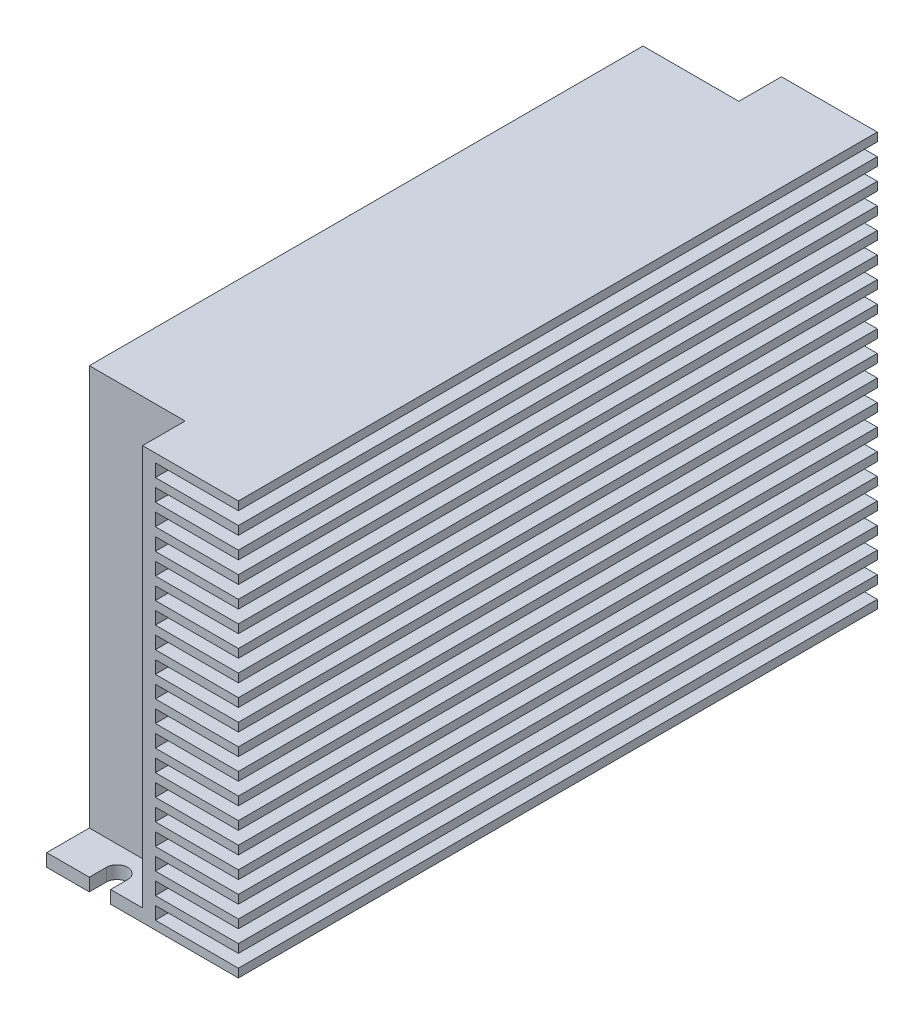
SolidWorks part; units mm, degrees
ref_plane "Front Plane" through (0, 0, 0) normal (0, 0, 1) x (1, 0, 0)
ref_plane "Top Plane" through (0, 0, 0) normal (0, 1, 0) x (1, 0, 0)
ref_plane "Right Plane" through (0, 0, 0) normal (1, 0, 0) x (0, 0, -1)
sketch "Sketch1" plane through (0, 0, 0) normal (0, 1, 0) x (1, 0, 0)
  line L1 (0, 0) -> (45, 0)
  line L2 (0, 0) -> (0, 150)
  line L3 (0, 150) -> (45, 150)
  line L4 (45, 0) -> (45, 150)
  dimension "D1" = 45
  dimension "D2" = 150
extrude "Boss-Extrude1" add sketch "Sketch1" along normal blind 97
sketch "Sketch2" plane through (0, 97, 0) normal (0, 1, 0) x (1, 0, 0)
  line L1 (0, 150) -> (22.5, 150)
  line L2 (0, 150) -> (0, 140)
  line L3 (0, 140) -> (22.5, 140)
  line L4 (22.5, 150) -> (22.5, 140)
  dimension "D1" = 22.5
  dimension "D2" = 10
extrude "Cut-Extrude1" cut sketch "Sketch2" against normal offset from surface (94 mm away) 3 up to face at (22.5, 0, -75)
sketch "Sketch3" plane through (0, 3, 0) normal (0, 1, 0) x (1, 0, 0)
  line L0 (10, 150) -> (10, 146)
  line L1 (22.5, 150) -> (0, 150) construction
  line L2 (15, 146) -> (15, 150)
  line L3 (15, 150) -> (10, 150)
  arc A0 (10, 146) -> (15, 146) centre (12.5, 146) ccw
  dimension "D1" = 6.5
  dimension "D3" = 2.5
  dimension "D2" = 12.5
extrude "Cut-Extrude2" cut sketch "Sketch3" against normal through all
ref_plane "Plane1" through (0, 0, -75) normal (0, 0, 1) x (1, 0, 0)
mirror "Mirror1" about plane through (0, 0, -75) normal (0, 0, 1) of "Cut-Extrude2", "Cut-Extrude1"
sketch "Sketch4" plane through (0, 0, 0) normal (0, 0, 1) x (1, 0, 0)
  line L0 (45, 97) -> (45, 0) construction
  line L1 (45, 95) -> (25.5, 95)
  line L2 (45, 95) -> (45, 92)
  line L3 (45, 92) -> (25.5, 92)
  line L4 (25.5, 95) -> (25.5, 92)
  line L5 (22.5, 3) -> (22.5, 97) construction
  dimension "D1" = 3
  dimension "D2" = 2
  dimension "D3" = 3
extrude "Cut-Extrude3" cut sketch "Sketch4" against normal through all
pattern_linear "LPattern1" count 19 spacing 5 along (0, -1, 0) of "Cut-Extrude3"
equation "\"D1@Sketch2\"=45/2"
